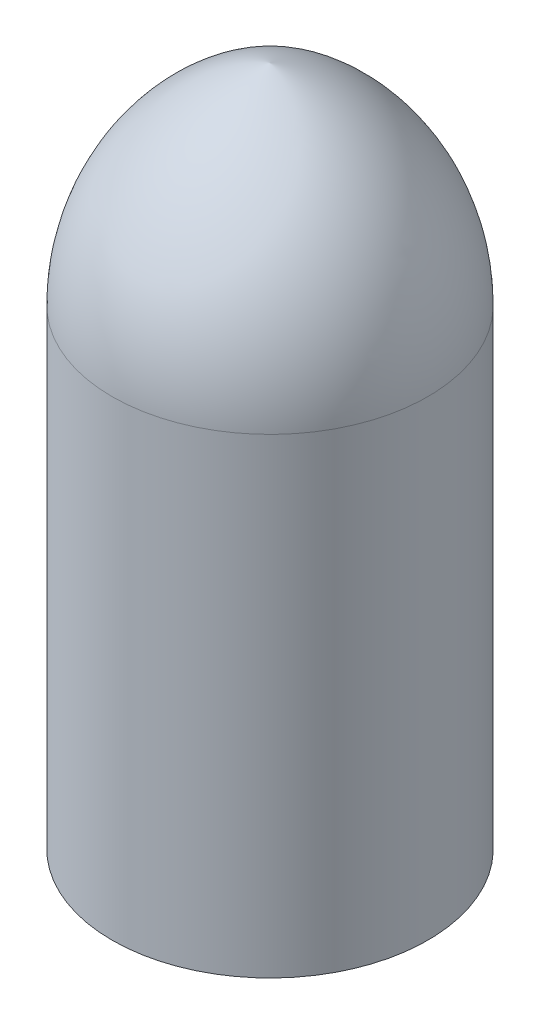
SolidWorks part; units mm, degrees
ref_plane "Front Plane" through (0, 0, 0) normal (0, 0, 1) x (1, 0, 0)
ref_plane "Top Plane" through (0, 0, 0) normal (0, 1, 0) x (1, 0, 0)
ref_plane "Right Plane" through (0, 0, 0) normal (1, 0, 0) x (0, 0, -1)
sketch "Sketch1" plane through (0, 0, 0) normal (0, 0, 1) x (1, 0, 0)
  line L0 (61, 0) -> (61, 170)
  line L1 (58, 0) -> (58, 170)
  line L4 (57, 0) -> (57, 170)
  line L5 (55, 0) -> (55, 170)
  line L6 (52, 0) -> (52, 170)
  line L7 (0, 240.6239) -> (0, 250)
  line L8 (52, 0) -> (61, 0)
  arc A0 (61, 170) -> (0, 250) centre (-21.959, 170) ccw
  arc A1 (58, 170) -> (0, 246.8846) centre (-21.959, 170) ccw
  arc A2 (57, 170) -> (0, 245.8441) centre (-21.959, 170) ccw
  arc A3 (55, 170) -> (0, 243.7597) centre (-21.959, 170) ccw
  arc A4 (52, 170) -> (0, 240.6239) centre (-21.959, 170) ccw
  arc A5 (52, 170) -> (-2.3823, 241.321) centre (-21.959, 170) ccw construction
  arc A6 (55, 170) -> (-1.5882, 244.214) centre (-21.959, 170) ccw construction
  arc A7 (57, 170) -> (-1.0588, 246.1427) centre (-21.959, 170) ccw construction
  arc A8 (58, 170) -> (-0.7941, 247.107) centre (-21.959, 170) ccw construction
  dimension "D1" = 170
  dimension "D6" = 2
  dimension "D2" = 61
  dimension "D3" = 80
  dimension "D4" = 3
  dimension "D5" = 1
  dimension "D7" = 3
revolve "Revolve3" add sketch "Sketch1" angle 360 about L7
